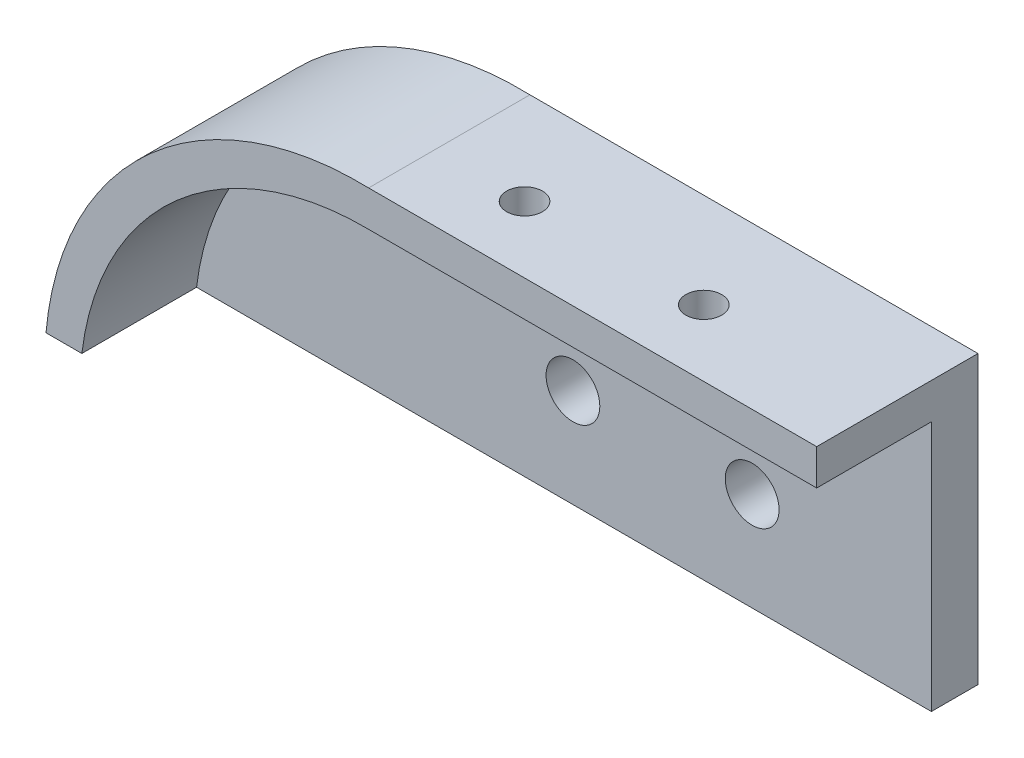
SolidWorks part; units mm, degrees
ref_plane "Alzado" through (0, 0, 0) normal (0, 0, 1) x (1, 0, 0)
ref_plane "Planta" through (0, 0, 0) normal (0, 1, 0) x (1, 0, 0)
ref_plane "Vista lateral" through (0, 0, 0) normal (1, 0, 0) x (0, 0, -1)
ref_plane "Plano1" through (0, 0, 4.5) normal (0, 0, 1) x (1, 0, 0)
sketch "Croquis1" plane through (0, 0, 4.5) normal (0, 0, 1) x (1, 0, 0)
  line L0 (-9, 0) -> (12.5, 0)
  line L1 (12.5, 0) -> (12.5, 8)
  line L2 (12.5, 8) -> (0, 8)
  arc A0 (0, 8) -> (-9, 0) centre (-0.2571, -0.7732) ccw
extrude "Saliente-Extruir1" add sketch "Croquis1" against normal blind 4.5
sketch "Croquis2" plane through (0, 0, 4.5) normal (0, 0, 1) x (1, 0, 0)
  line L0 (12.5, 7) -> (0, 7)
  line L1 (-8, 0) -> (12.5, 0)
  line L2 (12.5, 0) -> (12.5, 7)
  arc A0 (0, 7) -> (-8, 0) centre (-0.1033, -0.9533) ccw
extrude "Cortar-Extruir1" cut sketch "Croquis2" against normal blind 3.2
hole_wizard "Diámetro de taladro Ø1.0 (1)1" positions "Croquis4" profile "Croquis3" hole size "Ø1.0" standard "Ansi Metric"
sketch "Croquis4" plane through (0, 8, 0) normal (0, 1, 0) x (1, 0, 0)
  point P0 (2.5, -2.65)
  point P1 (7.5, -2.65)
sketch "Croquis3" plane through (2.5, 8, 2.65) normal (1, 0, 0) x (0, 0, 1)
  line L0 (0, 0) -> (0, 8)
  line L1 (0, 8) -> (0.5, 8)
  line L2 (0.5, 8) -> (0.5, 0)
  line L5 (0.5, 0) -> (0, 0)
  line L11 (0, -6.35) -> (0, 107.95) construction
  dimension "Diámetro de taladro hasta el siguiente" = 1
  dimension "Profundidad de taladro hasta el siguiente" = 8
hole_wizard "Diámetro de taladro Ø1.5 (1.5)1" positions "Croquis6" profile "Croquis5" hole size "Ø1.5" standard "Ansi Metric"
sketch "Croquis6" plane through (0, 0, 1.3) normal (0, 0, 1) x (1, 0, 0)
  point P0 (7.5, 2.75)
  point P1 (2.5, 2.75)
sketch "Croquis5" plane through (7.5, 2.75, 1.3) normal (1, 0, 0) x (0, -1, 0)
  line L0 (0, 0) -> (0, 1.3)
  line L1 (0, 1.3) -> (0.75, 1.3)
  line L2 (0.75, 1.3) -> (0.75, 0)
  line L5 (0.75, 0) -> (0, 0)
  line L11 (0, -6.35) -> (0, 107.95) construction
  dimension "Diámetro de taladro hasta el siguiente" = 1.5
  dimension "Profundidad de taladro hasta el siguiente" = 1.3
